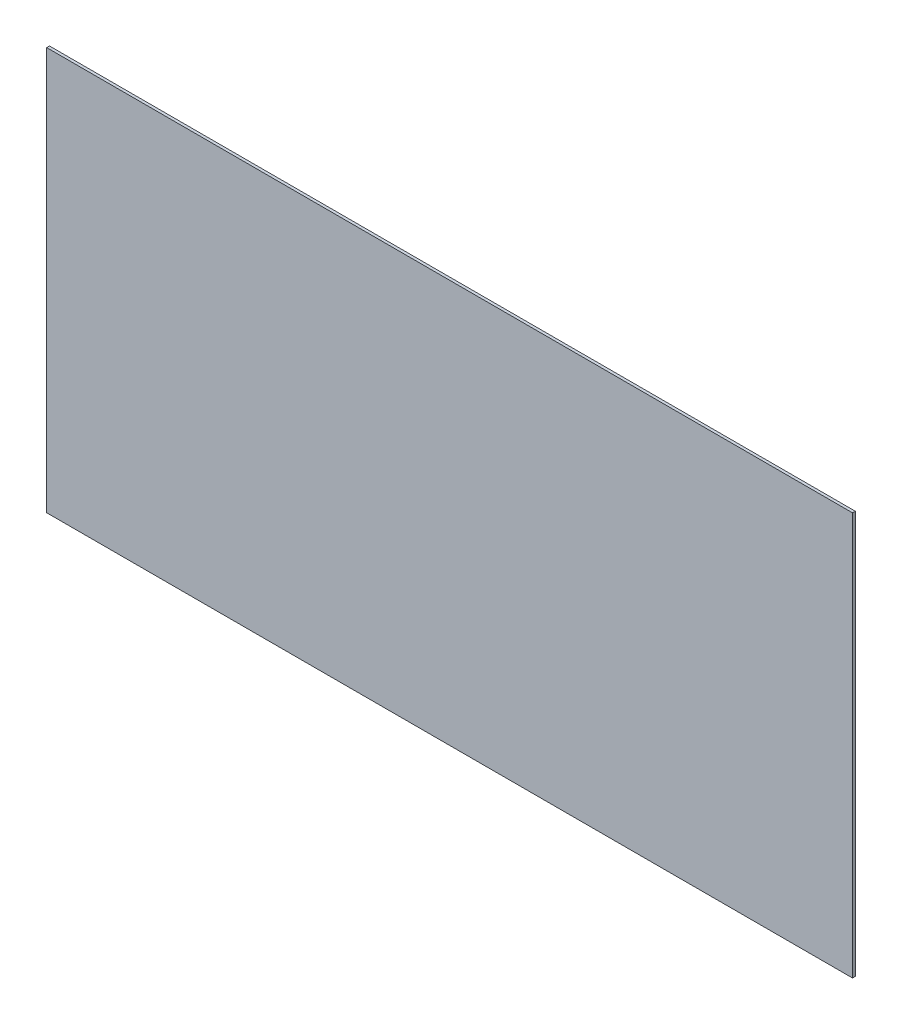
SolidWorks part; units mm, degrees
material "Acrylic (Medium-high impact)"
ref_plane "Front Plane" through (0, 0, 0) normal (0, 0, 1) x (1, 0, 0)
ref_plane "Top Plane" through (0, 0, 0) normal (0, 1, 0) x (1, 0, 0)
ref_plane "Right Plane" through (0, 0, 0) normal (1, 0, 0) x (0, 0, -1)
sketch "Sketch1" plane through (0, 0, 0) normal (0, 0, 1) x (1, 0, 0)
  line L1 (-914.4, -457.2) -> (914.4, -457.2)
  line L2 (-914.4, -457.2) -> (-914.4, 457.2)
  line L3 (-914.4, 457.2) -> (914.4, 457.2)
  line L4 (914.4, -457.2) -> (914.4, 457.2)
  line L5 (-914.4, -457.2) -> (914.4, 457.2) construction
  line L6 (-914.4, 457.2) -> (914.4, -457.2) construction
  point P0 (0, 0)
  dimension "D1" = 914.4
  dimension "D2" = 1828.8
extrude "Boss-Extrude1" add sketch "Sketch1" along normal blind 6.35
